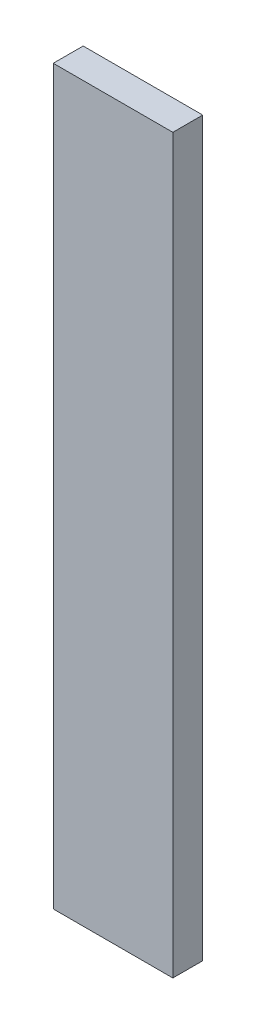
SolidWorks part; units mm, degrees
ref_plane "Front Plane" through (0, 0, 0) normal (0, 0, 1) x (1, 0, 0)
ref_plane "Top Plane" through (0, 0, 0) normal (0, 1, 0) x (1, 0, 0)
ref_plane "Right Plane" through (0, 0, 0) normal (1, 0, 0) x (0, 0, -1)
sketch "Sketch1" plane through (0, 0, 0) normal (0, 0, 1) x (1, 0, 0)
  line L1 (-25.4, 155.575) -> (25.4, 155.575)
  line L2 (-25.4, 155.575) -> (-25.4, -155.575)
  line L3 (-25.4, -155.575) -> (25.4, -155.575)
  line L4 (25.4, 155.575) -> (25.4, -155.575)
  line L5 (0, -155.575) -> (0, 155.575) construction
  line L6 (-25.4, 0) -> (25.4, 0) construction
  point P0 (0, 0)
  dimension "D1" = 311.15
  dimension "D2" = 50.8
extrude "Boss-Extrude1" add sketch "Sketch1" along normal blind 12.7
